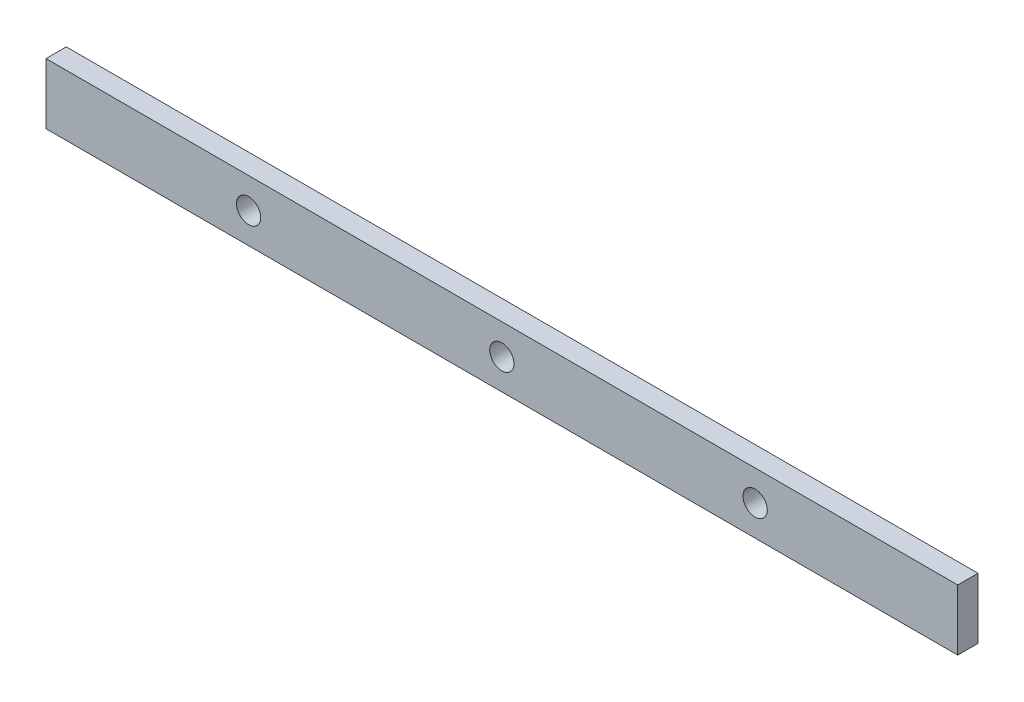
SolidWorks part; units mm, degrees
ref_plane "Plano frontal" through (0, 0, 0) normal (0, 0, 1) x (1, 0, 0)
ref_plane "Plano superior" through (0, 0, 0) normal (0, 1, 0) x (1, 0, 0)
ref_plane "Plano direito" through (0, 0, 0) normal (1, 0, 0) x (0, 0, -1)
sketch "Esboço1" plane through (0, 0, 0) normal (0, 0, 1) x (1, 0, 0)
  line L1 (0, 0) -> (450, 0)
  line L2 (0, 0) -> (0, 30)
  line L3 (0, 30) -> (450, 30)
  line L4 (450, 0) -> (450, 30)
  dimension "D1" = 450
  dimension "D2" = 30
extrude "Ressalto-extrusão1" add sketch "Esboço1" along normal blind 10
sketch "Esboço2" plane through (0, 0, 10) normal (0, 0, 1) x (1, 0, 0)
  line L0 (225, 30) -> (225, 0) construction
  line L1 (450, 30) -> (0, 30) construction
  line L2 (0, 0) -> (450, 0) construction
  line L3 (350, 30) -> (350, 0) construction
  circle A0 centre (225, 15) radius 6
  circle A1 centre (350, 15) radius 6
  circle A2 centre (100, 15) radius 6
  dimension "D1" = 12
  dimension "D2" = 12
  dimension "D3" = 125
extrude "Corte-extrusão1" cut sketch "Esboço2" against normal through all
